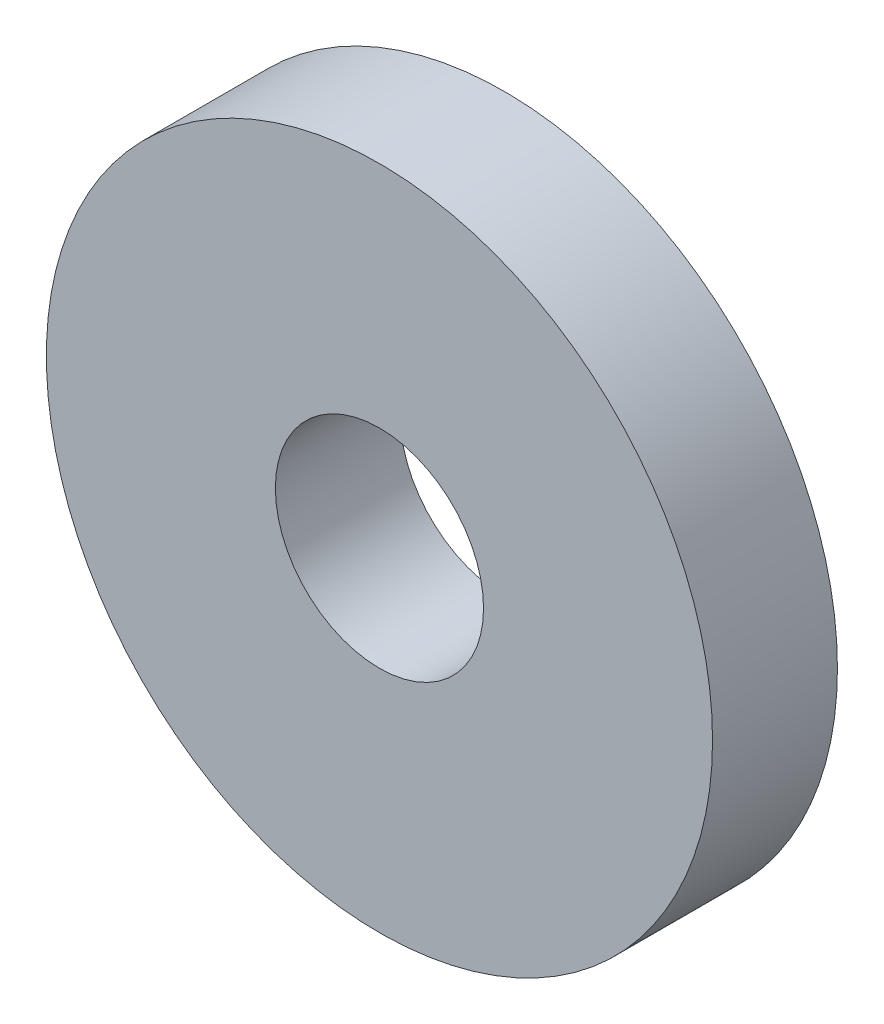
SolidWorks part; units mm, degrees
ref_plane "Front Plane" through (0, 0, 0) normal (0, 0, 1) x (1, 0, 0)
ref_plane "Top Plane" through (0, 0, 0) normal (0, 1, 0) x (1, 0, 0)
ref_plane "Right Plane" through (0, 0, 0) normal (1, 0, 0) x (0, 0, -1)
sketch "Sketch1" plane through (0, 0, 0) normal (0, 0, 1) x (1, 0, 0)
  circle A0 centre (0, 0) radius 8
extrude "Boss-Extrude1" add sketch "Sketch1" along normal blind 3
sketch "Sketch2" plane through (0, 0, 3) normal (0, 0, 1) x (1, 0, 0)
  circle A0 centre (0, 0) radius 2.5
  dimension "D1" = 5
extrude "Cut-Extrude1" cut sketch "Sketch2" against normal blind 3
